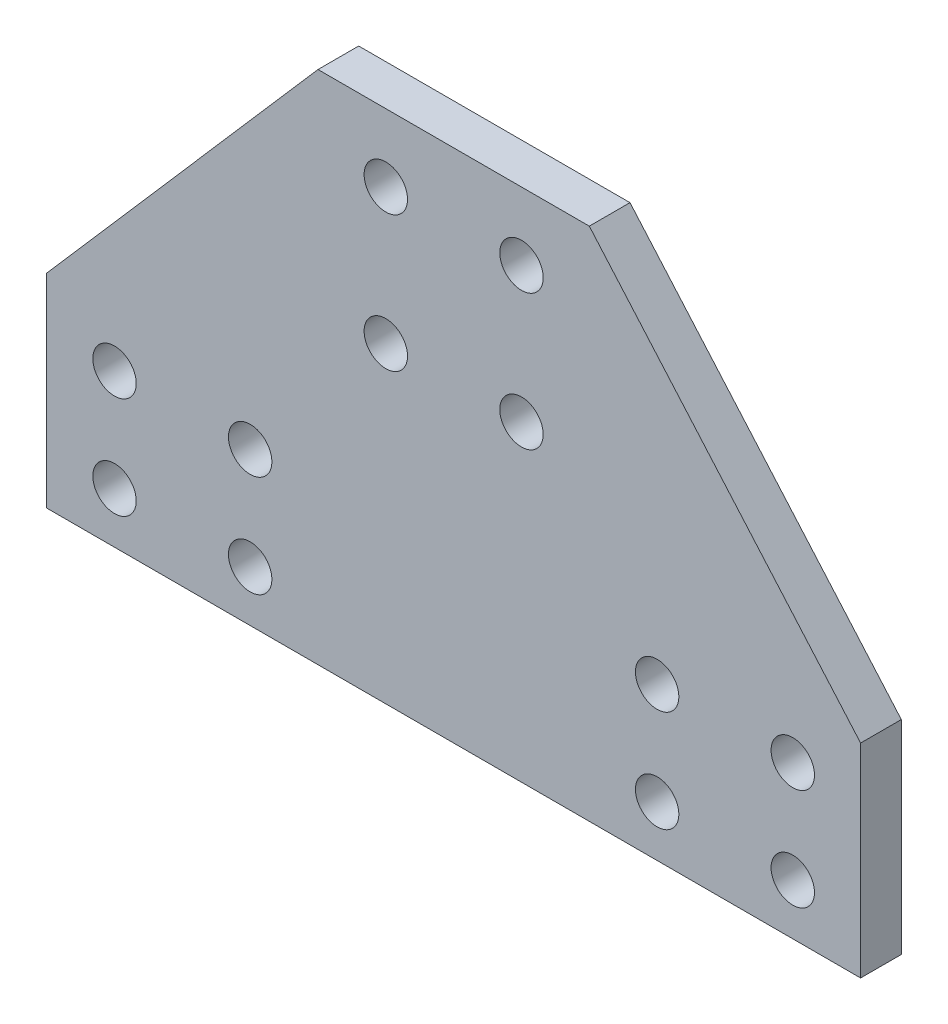
SolidWorks part; units mm, degrees
ref_plane "前视基准面" through (0, 0, 0) normal (0, 0, 1) x (1, 0, 0)
ref_plane "上视基准面" through (0, 0, 0) normal (0, 1, 0) x (1, 0, 0)
ref_plane "右视基准面" through (0, 0, 0) normal (1, 0, 0) x (0, 0, -1)
other "Configuration Table"
sketch "草图1" plane through (0, 0, 0) normal (0, 0, 1) x (1, 0, 0)
  line L0 (0, 0) -> (20, 0)
  line L1 (20, 0) -> (40, -23)
  line L2 (40, -23) -> (40, -38)
  line L3 (40, -38) -> (-20, -38)
  line L4 (-20, -38) -> (-20, -23)
  line L5 (-20, -23) -> (0, 0)
  line L6 (10, 0) -> (10, -38) construction
  dimension "D1" = 15
  dimension "D2" = 15
  dimension "D3" = 20
  dimension "D4" = 60
  dimension "D5" = 23
extrude "凸台-拉伸1" add sketch "草图1" along normal blind 3
sketch "草图2" plane through (0, 0, 3) normal (0, 0, 1) x (1, 0, 0)
  line L0 (10, 0) -> (10, -38) construction
  line L1 (20, 0) -> (0, 0) construction
  line L2 (-20, -38) -> (40, -38) construction
  line L3 (-20, -30.5) -> (40, -30.5) construction
  line L4 (-20, -23) -> (-20, -38) construction
  line L5 (40, -38) -> (40, -23) construction
  line L6 (-10, -30.5) -> (-10, -38) construction
  line L7 (10, -10) -> (28.6957, -10) construction
  line L8 (40, -23) -> (20, 0) construction
  circle A0 centre (-15, -34.25) radius 1.6
  circle A1 centre (-15, -26.75) radius 1.6
  circle A2 centre (-5, -34.25) radius 1.6
  circle A3 centre (-5, -26.75) radius 1.6
  circle A4 centre (25, -34.25) radius 1.6
  circle A5 centre (35, -34.25) radius 1.6
  circle A6 centre (25, -26.75) radius 1.6
  circle A7 centre (35, -26.75) radius 1.6
  circle A8 centre (5, -5) radius 1.6
  circle A9 centre (15, -5) radius 1.6
  circle A10 centre (15, -15) radius 1.6
  circle A11 centre (5, -15) radius 1.6
  dimension "D1" = 3.2
  dimension "D5" = 10
  dimension "D6" = 3.2
  dimension "D2" = 5
  dimension "D3" = 10
  dimension "D4" = 3.75
  dimension "D7" = 5
  dimension "D8" = 5
extrude "切除-拉伸1" cut sketch "草图2" against normal through all
